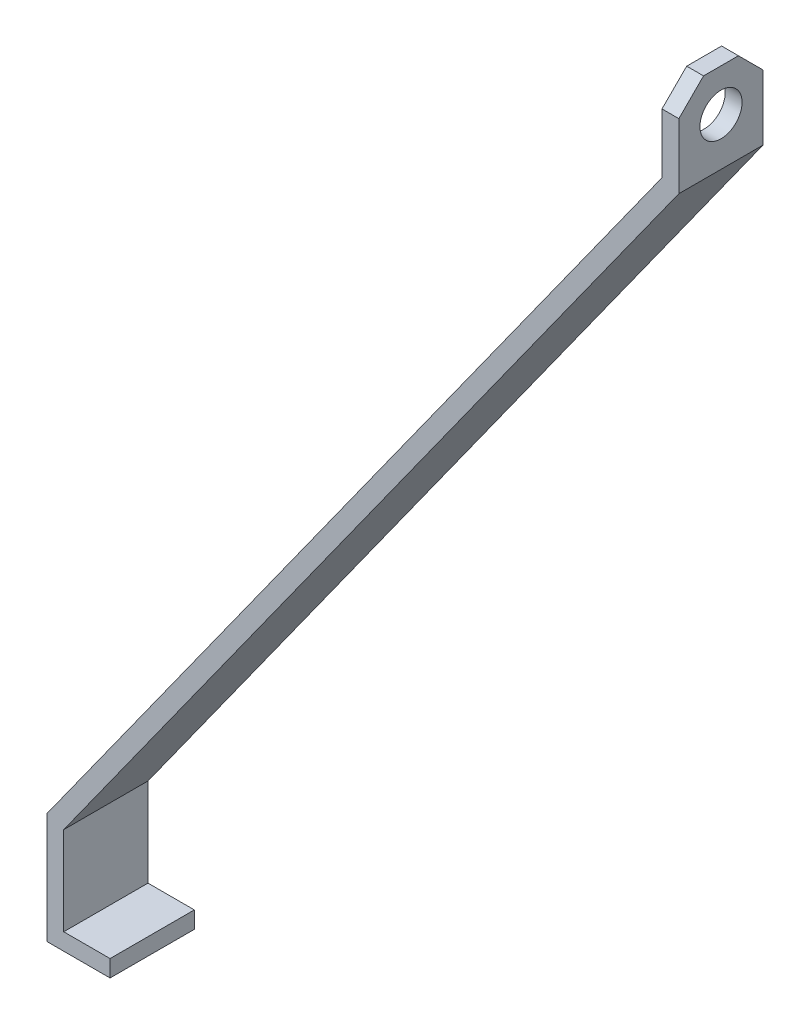
SolidWorks part; units mm, degrees
ref_plane "Front" through (0, 0, 0) normal (0, 0, 1) x (1, 0, 0)
ref_plane "Top" through (0, 0, 0) normal (0, 1, 0) x (1, 0, 0)
ref_plane "Right" through (0, 0, 0) normal (1, 0, 0) x (0, 0, -1)
sketch "Sketch1" plane through (0, 0, 0) normal (0, 0, 1) x (1, 0, 0)
  line L0 (0, 0) -> (0, -8)
  line L1 (0, -8) -> (-58.4, -89.4859)
  line L2 (-58.4, -89.4859) -> (-58.4, -100)
  line L3 (-58.4, -100) -> (-52.4, -100)
  line L4 (-56.8, -90) -> (-56.8, -98.4)
  line L5 (-56.8, -90) -> (1.6, -8.5141)
  line L6 (1.6, -8.5141) -> (1.6, 0)
  line L7 (1.6, 0) -> (0, 0)
  line L8 (-56.8, -98.4) -> (-52.4, -98.4)
  line L9 (-52.4, -98.4) -> (-52.4, -100)
  dimension "D1" = 1.6
  dimension "D2" = 1.6
  dimension "D3" = 1.6
  dimension "D4" = 8
  dimension "D5" = 10
  dimension "D6" = 100
  dimension "D7" = 60
  dimension "D8" = 1.6
  dimension "D9" = 6
extrude "Boss-Extrude1" add sketch "Sketch1" along normal blind 8
sketch "Sketch2" plane through (0, 0, 0) normal (-1, 0, 0) x (0, 0, 1)
  line L0 (0, 0) -> (0, -2.3431)
  line L1 (0, 0) -> (0, -8) construction
  line L3 (0, -2.3431) -> (2.3431, 0)
  line L4 (8, 0) -> (0, 0) construction
  line L5 (2.3431, 0) -> (0, 0)
  line L6 (8, -2.3431) -> (5.6569, 0)
  line L7 (8, 0) -> (8, -8) construction
  line L8 (5.6569, 0) -> (8, 0)
  line L9 (8, 0) -> (8, -2.3431)
  circle A0 centre (4, -4) radius 2
  point P14 (4, 0)
  point P17 (8, -4)
  dimension "D1" = 4
  dimension "D2" = 135
  dimension "D3" = 135
  dimension "D4" = 4
  dimension "D5" = 4
extrude "Cut-Extrude1" cut sketch "Sketch2" against normal through all
